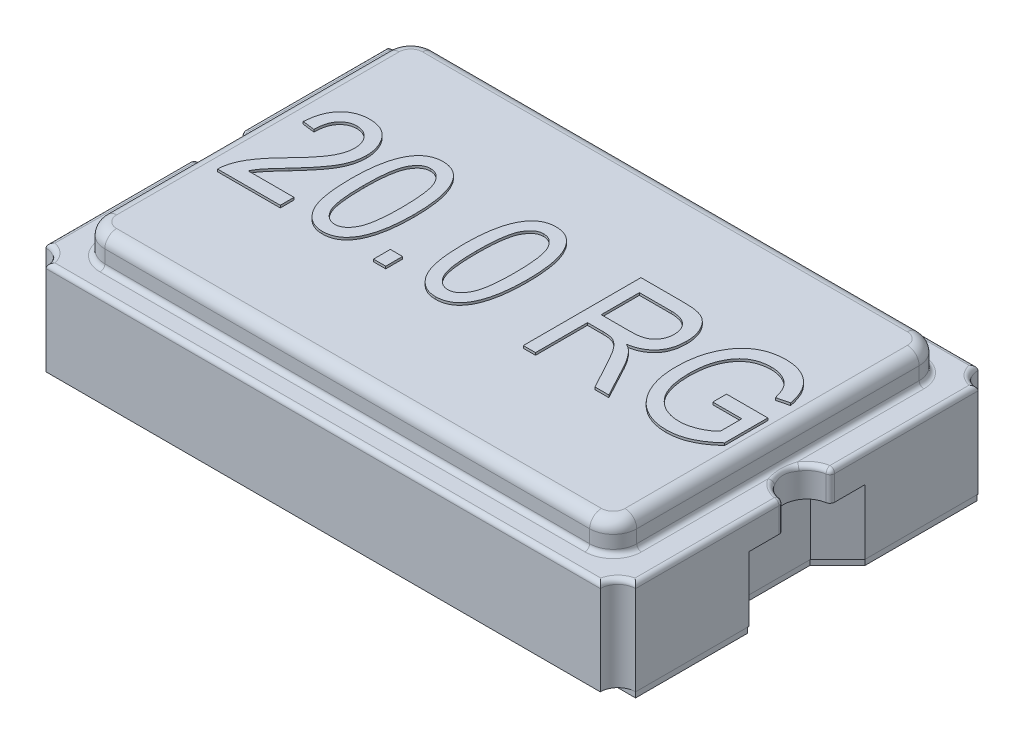
SolidWorks part; units mm, degrees
ref_plane "Спереди" through (0, 0, 0) normal (0, 0, 1) x (1, 0, 0)
ref_plane "Сверху" through (0, 0, 0) normal (0, 1, 0) x (1, 0, 0)
ref_plane "Справа" through (0, 0, 0) normal (1, 0, 0) x (0, 0, -1)
sketch "Эскиз1" plane through (0, 0, 0) normal (0, 1, 0) x (1, 0, 0)
  line L0 (-4.9024, 0) -> (3.8128, 0) construction
  line L1 (2.5, -1.6) -> (-2.5, -1.6) construction
  line L2 (2.5, -1.6) -> (2.5, 1.6) construction
  line L3 (2.5, 1.6) -> (-2.5, 1.6) construction
  line L4 (-2.5, -1.6) -> (-2.5, 1.6) construction
  line L5 (2.5, -1.6) -> (-2.5, 1.6) construction
  line L6 (2.5, 1.6) -> (-2.5, -1.6) construction
  line L7 (0, 0) -> (0, 2.9816) construction
  line L8 (2.5, -1.45) -> (1.2, -1.45) construction
  line L9 (-2.5, 1.45) -> (-1.2, 1.45) construction
  line L10 (-2.5, 1.45) -> (-2.5, -1.45) construction
  line L11 (-2.5, -1.45) -> (-1.2, -1.45) construction
  line L12 (-1.2, 1.45) -> (-1.2, -1.45) construction
  line L13 (1.2, 1.45) -> (1.2, -1.45) construction
  line L14 (2.5, 1.45) -> (2.5, -1.45) construction
  line L15 (2.5, 1.45) -> (1.2, 1.45) construction
  line L16 (-2.2656, 1.45) -> (-2.2656, -1.4625) construction
  line L17 (2.2656, 1.45) -> (2.2656, -1.4625) construction
  line L18 (-2.5, 0.5) -> (-2.5, 1.45)
  line L19 (2.5, -0.5) -> (-2.5, -0.5) construction
  line L20 (2.5, -0.5) -> (2.5, 0.5) construction
  line L21 (2.5, 0.5) -> (-2.5, 0.5) construction
  line L22 (-2.5, -0.5) -> (-2.5, 0.5) construction
  line L23 (2.5, -0.5) -> (-2.5, 0.5) construction
  line L24 (2.5, 0.5) -> (-2.5, -0.5) construction
  line L25 (-2.5, 1.45) -> (-1.2, 1.45)
  line L26 (-1.2, 1.45) -> (-1.2, -1.45)
  line L27 (-1.2, -1.45) -> (-2.5, -1.45)
  line L28 (-2.5, -1.45) -> (-2.5, -0.5)
  line L29 (-2.5, -0.5) -> (-2.2656, -0.2656)
  line L30 (-2.2656, -0.2656) -> (-2.2656, 0.2656)
  line L31 (-2.2656, 0.2656) -> (-2.5, 0.5)
  line L32 (2.5, 0.5) -> (2.5, 1.45)
  line L33 (2.2656, 0.2656) -> (2.5, 0.5)
  line L34 (2.2656, -0.2656) -> (2.2656, 0.2656)
  line L35 (2.5, -0.5) -> (2.2656, -0.2656)
  line L36 (2.5, -1.45) -> (2.5, -0.5)
  line L37 (1.2, -1.45) -> (2.5, -1.45)
  line L38 (1.2, 1.45) -> (1.2, -1.45)
  line L39 (2.5, 1.45) -> (1.2, 1.45)
  dimension "D1" = 3.2
  dimension "D2" = 5
  dimension "D3" = 1.3
  dimension "D4" = 2.9
  dimension "D5" = 2.4
  dimension "D6" = 0.15
  dimension "D7" = 1
  dimension "D8" = 5
extrude "Вытянуть6" add sketch "Эскиз1" along normal blind 0.05
sketch "Эскиз10" plane through (0, 0.05, 0) normal (0, 1, 0) x (1, 0, 0)
  line L0 (-2.355, 1.605) -> (2.355, 1.605)
  line L1 (2.505, -1.605) -> (-2.505, -1.605) construction
  line L2 (2.505, -1.605) -> (2.505, 1.605) construction
  line L3 (2.505, 1.605) -> (-2.505, 1.605) construction
  line L4 (-2.505, -1.605) -> (-2.505, 1.605) construction
  line L5 (2.505, -1.605) -> (-2.505, 1.605) construction
  line L6 (2.505, 1.605) -> (-2.505, -1.605) construction
  line L7 (0, 1.7981) -> (0, -1.7052) construction
  line L8 (0, 1.7094) -> (0, -1.7644) construction
  line L9 (-2.638, 0) -> (2.7298, 0) construction
  line L10 (-2.7362, 0) -> (2.8018, 0) construction
  line L11 (-2.505, 1.455) -> (-2.505, 0.4927)
  line L12 (-2.505, 0.4927) -> (-2.2734, 0.2611)
  line L13 (-2.2734, 0.2611) -> (-2.2734, -0.2608)
  line L14 (-2.2734, -0.2608) -> (-2.505, -0.4924)
  line L15 (-2.505, -0.4924) -> (-2.505, -1.455)
  line L16 (-2.355, -1.605) -> (2.355, -1.605)
  line L17 (2.505, -0.4924) -> (2.505, -1.455)
  line L18 (2.2734, -0.2608) -> (2.505, -0.4924)
  line L19 (2.2734, 0.2611) -> (2.2734, -0.2608)
  line L20 (2.505, 0.4927) -> (2.2734, 0.2611)
  line L21 (2.505, 1.455) -> (2.505, 0.4927)
  arc A0 (-2.355, 1.605) -> (-2.505, 1.455) centre (-2.505, 1.605) cw
  arc A1 (-2.505, 1.455) -> (-2.355, 1.605) centre (-2.505, 1.605) ccw construction
  arc A2 (2.355, 1.605) -> (2.505, 1.455) centre (2.505, 1.605) ccw
  arc A3 (2.355, -1.605) -> (2.505, -1.455) centre (2.505, -1.605) cw
  arc A4 (-2.355, -1.605) -> (-2.505, -1.455) centre (-2.505, -1.605) ccw
  point P0 (0, 0)
  dimension "D3" = 0.15
  dimension "D1" = 5.01
  dimension "D2" = 3.21
  dimension "D4" = 0.9623
  dimension "D5" = 0.5219
  dimension "D6" = 0.9626
  dimension "D7" = 0.3275
extrude "Вытянуть21" add sketch "Эскиз10" along normal blind 0.55
ref_plane "Плоскость1" through (0, 0.6, 1.605) normal (0, 1, 0) x (-1, 0, 0)
sketch "Эскиз9" plane through (0, 0.6, 1.605) normal (0, 1, 0) x (-1, 0, 0)
  line L0 (2.6188, -1.605) -> (-4.0018, -1.605) construction
  line L1 (-2.355, -3.21) -> (2.355, -3.21) construction
  line L2 (0, -3.1594) -> (0, 0.1236) construction
  line L3 (2.505, -3.06) -> (2.505, -2.0977) construction
  line L4 (2.355, -3.21) -> (-2.355, -3.21)
  line L5 (2.505, 0) -> (-2.505, -3.21) construction
  line L6 (2.505, -3.21) -> (-2.505, 0) construction
  line L7 (-2.505, -3.06) -> (-2.505, -1.805)
  line L8 (-2.505, -1.405) -> (-2.505, -0.15)
  line L9 (-2.355, 0) -> (2.355, 0)
  line L10 (2.505, -0.15) -> (2.505, -1.405)
  line L11 (2.505, -3.06) -> (2.505, -1.805)
  arc A0 (2.355, -3.21) -> (2.505, -3.06) centre (2.505, -3.21) cw
  arc A1 (-2.355, -3.21) -> (-2.505, -3.06) centre (-2.505, -3.21) ccw
  arc A3 (-2.355, 0) -> (-2.505, -0.15) centre (-2.505, 0) cw
  arc A4 (2.355, 0) -> (2.505, -0.15) centre (2.505, 0) ccw
  arc A5 (-2.505, -1.805) -> (-2.505, -1.405) centre (-2.505, -1.605) ccw
  arc A6 (2.505, -1.805) -> (2.505, -1.405) centre (2.505, -1.605) cw
  point P0 (0, -1.605)
  dimension "D3" = 0.2
  dimension "D1" = 5.01
  dimension "D2" = 3.21
extrude "Вытянуть22" add sketch "Эскиз9" along normal blind 0.25
sketch "Эскиз11" plane through (0, 0.85, 0) normal (0, 1, 0) x (1, 0, 0)
  line L1 (2.26, -1.4) -> (-2.26, -1.4)
  line L2 (2.26, -1.4) -> (2.26, 1.4)
  line L3 (2.26, 1.4) -> (-2.26, 1.4)
  line L4 (-2.26, -1.4) -> (-2.26, 1.4)
  line L5 (2.26, -1.4) -> (-2.26, 1.4) construction
  line L6 (2.26, 1.4) -> (-2.26, -1.4) construction
  point P0 (0, 0)
  dimension "D1" = 4.52
  dimension "D2" = 2.8
extrude "Вытянуть23" add sketch "Эскиз11" along normal blind 0.25
fillet "Скругление1" radius 0.2 4 edges at (2.26, 0.975, 1.4) (2.26, 0.975, -1.4) (-2.26, 0.975, -1.4) (-2.26, 0.975, 1.4)
fillet "Скругление2" radius 0.1 8 edges at (-2.2014, 1.1, 1.3414) (-2.26, 1.1, 0) (-2.2014, 1.1, -1.3414) (0, 1.1, -1.4) (2.2014, 1.1, -1.3414) (2.26, 1.1, 0) (2.2014, 1.1, 1.3414) (0, 1.1, 1.4)
fillet "Скругление5" radius 0.04 18 edges at (-2.2014, 0.85, 1.3414) (-2.26, 0.85, 0) (-2.2014, 0.85, -1.3414) (0, 0.85, -1.4) (2.2014, 0.85, -1.3414) (2.26, 0.85, 0) (2.2014, 0.85, 1.3414) (2.3989, 0.85, -1.4989) (-2.3989, 0.85, 1.4989) (-2.3989, 0.85, -1.4989) (0, 0.85, -1.605) (-2.505, 0.85, -0.8275) (-2.505, 0.85, 0.8275) (2.505, 0.85, -0.8275) (2.505, 0.85, 0.8275) (2.3989, 0.85, 1.4989) (0, 0.85, 1.605) (0, 0.85, 1.4)
fillet "Скругление6" radius 0.04 10 edges at (2.505, 0.705, 0.2) (2.4898, 0.8414, 0.1994) (2.505, 0.705, -0.2) (2.4962, 0.835, -0.1998) (-2.505, 0.705, -0.2) (-2.4898, 0.8414, -0.1994) (-2.505, 0.705, 0.2) (-2.4962, 0.835, 0.1998) (2.305, 0.85, 0) (-2.305, 0.85, 0)
sketch "Эскиз12" plane through (0, 1.1, 0) normal (0, 1, 0) x (1, 0, 0)
  line L0 (-2.1, -0.4535) -> (1.9364, -0.4535) construction
  text T0 "20.0 RG" font "Arial Narrow" height 1
extrude "Вытянуть24" add sketch "Эскиз12" along normal blind 0.02
